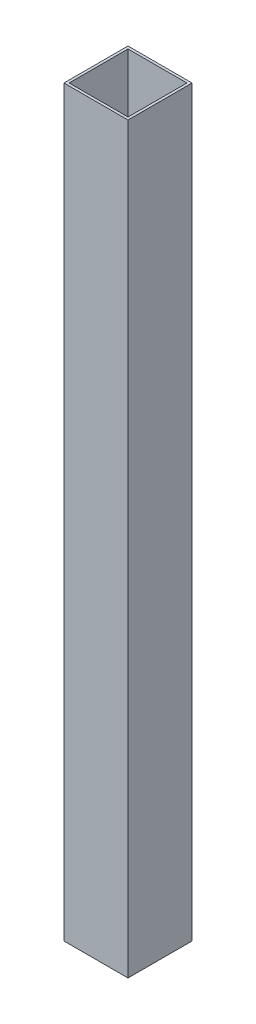
SolidWorks part; units mm, degrees
ref_plane "Front Plane" through (0, 0, 0) normal (0, 0, 1) x (1, 0, 0)
ref_plane "Top Plane" through (0, 0, 0) normal (0, 1, 0) x (1, 0, 0)
ref_plane "Right Plane" through (0, 0, 0) normal (1, 0, 0) x (0, 0, -1)
sketch "Sketch1" plane through (0, 0, 0) normal (0, 0, 1) x (1, 0, 0)
  line L1 (230.5701, -229.3861) -> (255.5701, -229.3861)
  line L2 (230.5701, -229.3861) -> (230.5701, 60.6139)
  line L3 (230.5701, 60.6139) -> (255.5701, 60.6139)
  line L4 (255.5701, -229.3861) -> (255.5701, 60.6139)
  dimension "D1" = 25
  dimension "D2" = 290
extrude "Boss-Extrude1" add sketch "Sketch1" along normal blind 25
sketch "Sketch2" plane through (0, 60.6139, 0) normal (0, 1, 0) x (1, 0, 0)
  line L0 (255.5701, -25) -> (255.5701, 0) construction
  line L1 (254.5701, -24) -> (231.5701, -24)
  line L2 (254.5701, -24) -> (254.5701, -1)
  line L3 (254.5701, -1) -> (231.5701, -1)
  line L4 (231.5701, -24) -> (231.5701, -1)
  line L5 (255.5701, -25) -> (230.5701, -25) construction
  dimension "D1" = 23
  dimension "D2" = 1
  dimension "D3" = 1
  dimension "D4" = 23
extrude "Cut-Extrude1" cut sketch "Sketch2" against normal through all
